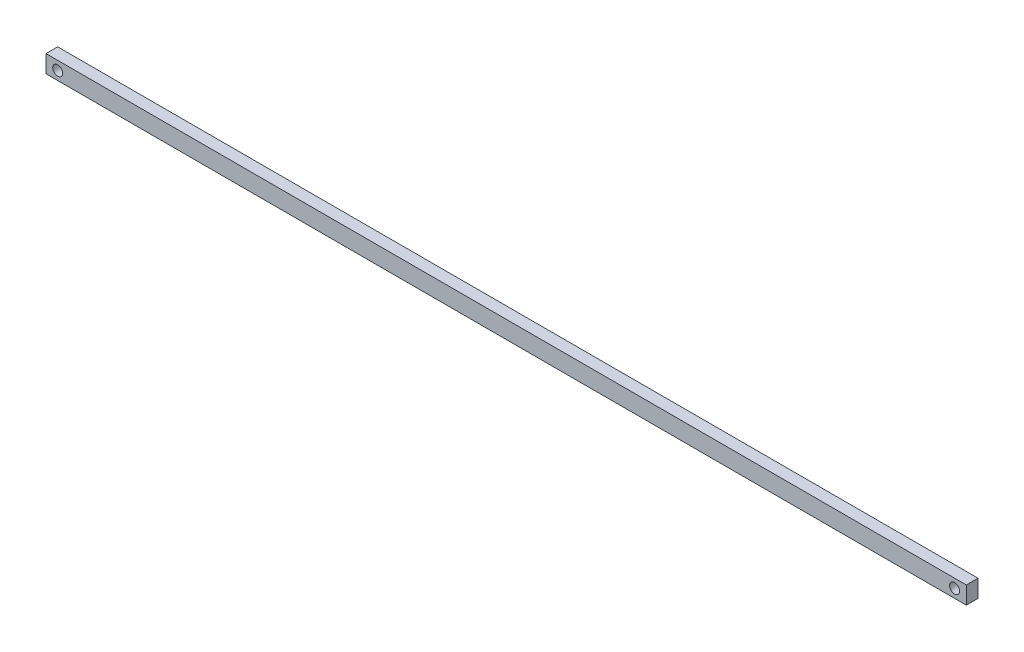
SolidWorks part; units mm, degrees
material "ASTM A36 Steel"
ref_plane "Front Plane" through (0, 0, 0) normal (0, 0, 1) x (1, 0, 0)
ref_plane "Top Plane" through (0, 0, 0) normal (0, 1, 0) x (1, 0, 0)
ref_plane "Right Plane" through (0, 0, 0) normal (1, 0, 0) x (0, 0, -1)
sketch "Sketch1" plane through (0, 0, 0) normal (0, 0, 1) x (1, 0, 0)
  line L0 (55, 0) -> (-55, 0) construction
  line L1 (0, 0) -> (788, 0)
  line L2 (0, 0) -> (0, 15)
  line L3 (0, 15) -> (788, 15)
  line L4 (788, 0) -> (788, 15)
  dimension "D1" = 788
  dimension "D2" = 15
extrude "Boss-Extrude1" add sketch "Sketch1" along normal blind 10
sketch "Sketch2" plane through (0, 0, 10) normal (0, 0, 1) x (1, 0, 0)
  line L0 (0, 15) -> (0, 0) construction
  line L1 (0, 7.5) -> (-51.7723, 7.5) construction
  line L3 (788, 0) -> (788, 15) construction
  circle A0 centre (10, 7.5) radius 4.255
  circle A1 centre (778, 7.5) radius 4.255
  dimension "D1" = 8.51
  dimension "D2" = 10
  dimension "D3" = 10
extrude "Cut-Extrude1" cut sketch "Sketch2" against normal up to surface (10 mm away) up to face at (394, 7.5, 0)
